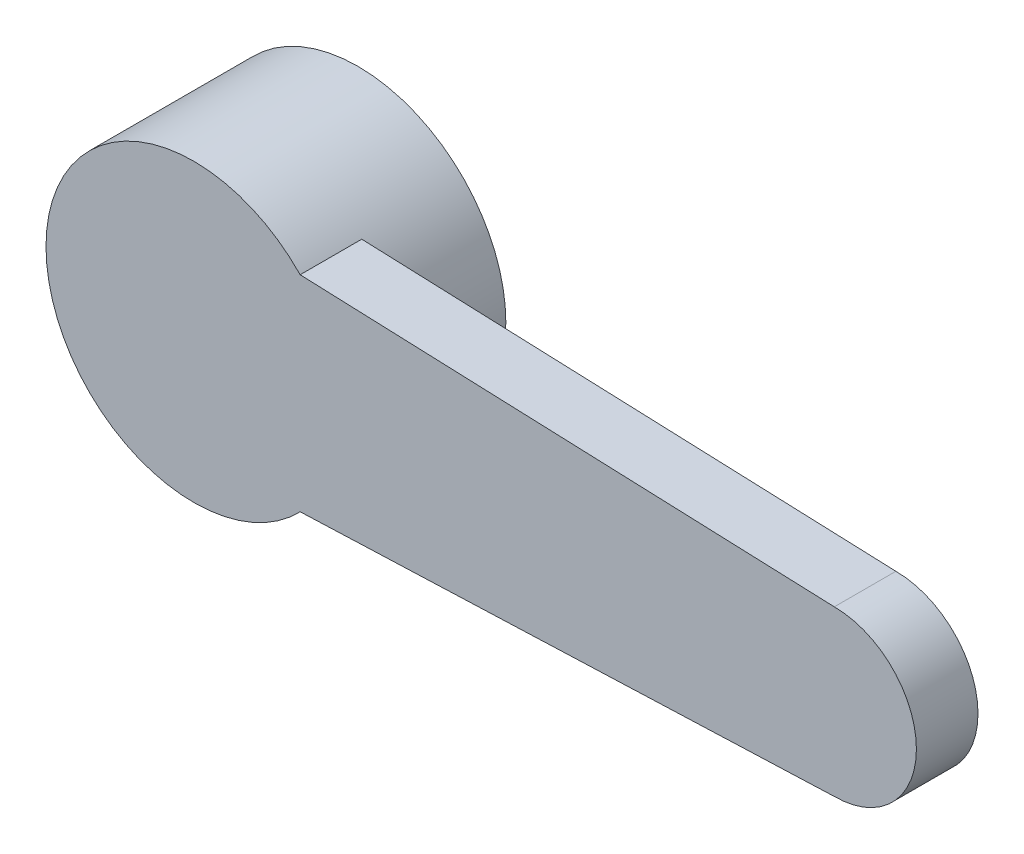
SolidWorks part; units mm, degrees
ref_plane "前视基准面" through (0, 0, 0) normal (0, 0, 1) x (1, 0, 0)
ref_plane "上视基准面" through (0, 0, 0) normal (0, 1, 0) x (1, 0, 0)
ref_plane "右视基准面" through (0, 0, 0) normal (1, 0, 0) x (0, 0, -1)
other "Configuration Table"
sketch "草图1" plane through (0, 0, 0) normal (0, 0, 1) x (1, 0, 0)
  circle A0 centre (0, 0) radius 3.6
  dimension "D1" = 7.2
extrude "凸台-拉伸1" add sketch "草图1" along normal blind 4
sketch "草图2" plane through (0, 0, 4) normal (0, 0, 1) x (1, 0, 0)
  line L0 (0, 0) -> (17.6, 0) construction
  line L1 (2.5904, 2.5) -> (15.6, 2)
  line L2 (15.6, -2) -> (15.6, 2) construction
  line L3 (2.5904, -2.5) -> (15.6, -2)
  line L4 (2.5904, -2.5) -> (2.5904, 2.5)
  circle A0 centre (0, 0) radius 3.6 construction
  arc A1 (15.6, 2) -> (15.6, -2) centre (15.6, 0) cw
  dimension "D3" = 15.6
  dimension "D4" = 2
  dimension "D1" = 4
  dimension "D2" = 5
extrude "凸台-拉伸2" add sketch "草图2" against normal blind 1.5
